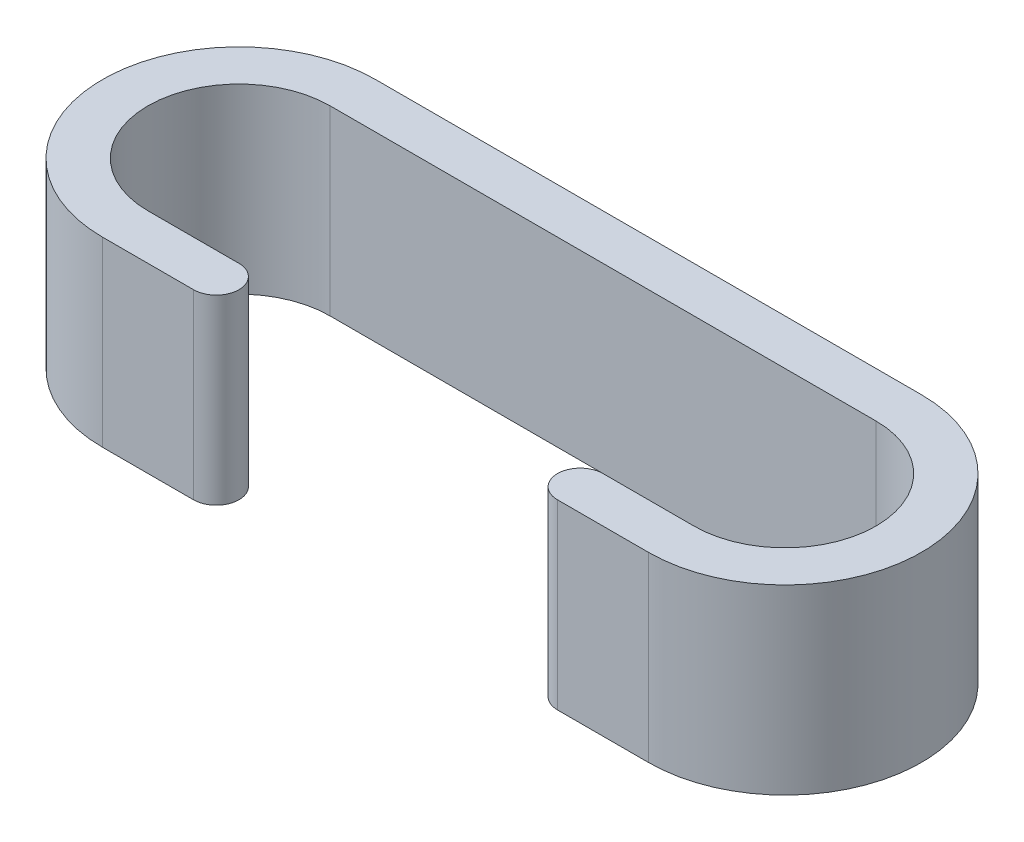
SolidWorks part; units mm, degrees
ref_plane "Front Plane" through (0, 0, 0) normal (0, 0, 1) x (1, 0, 0)
ref_plane "Top Plane" through (0, 0, 0) normal (0, 1, 0) x (1, 0, 0)
ref_plane "Right Plane" through (0, 0, 0) normal (1, 0, 0) x (0, 0, -1)
sketch "Sketch1" plane through (0, 0, 0) normal (0, 1, 0) x (1, 0, 0)
  line L0 (-6.35, 0) -> (-9.525, 0)
  line L1 (-9.525, 6.35) -> (9.525, 6.35)
  line L2 (9.525, 0) -> (6.35, 0)
  line L3 (-6.35, 0) -> (6.35, 0) construction
  line L4 (-6.35, -1.5875) -> (-9.525, -1.5875)
  line L5 (-9.525, 7.9375) -> (9.525, 7.9375)
  line L6 (9.525, -1.5875) -> (6.35, -1.5875)
  arc A0 (-9.525, 0) -> (-9.525, 6.35) centre (-9.525, 3.175) cw
  arc A1 (9.525, 6.35) -> (9.525, 0) centre (9.525, 3.175) cw
  arc A2 (-9.525, -1.5875) -> (-9.525, 7.9375) centre (-9.525, 3.175) cw
  arc A3 (9.525, 7.9375) -> (9.525, -1.5875) centre (9.525, 3.175) cw
  arc A4 (-6.35, 0) -> (-6.35, -1.5875) centre (-6.35, -0.7937) cw
  arc A5 (6.35, 0) -> (6.35, -1.5875) centre (6.35, -0.7937) ccw
  point P8 (0, 0)
  point P20 (-12.7, 3.175)
  point P21 (12.7, 3.175)
  dimension "D1" = 25.4
  dimension "D2" = 6.35
  dimension "D3" = 12.7
  dimension "D4" = 1.5875
extrude "Boss-Extrude1" add sketch "Sketch1" along normal blind 6.35
